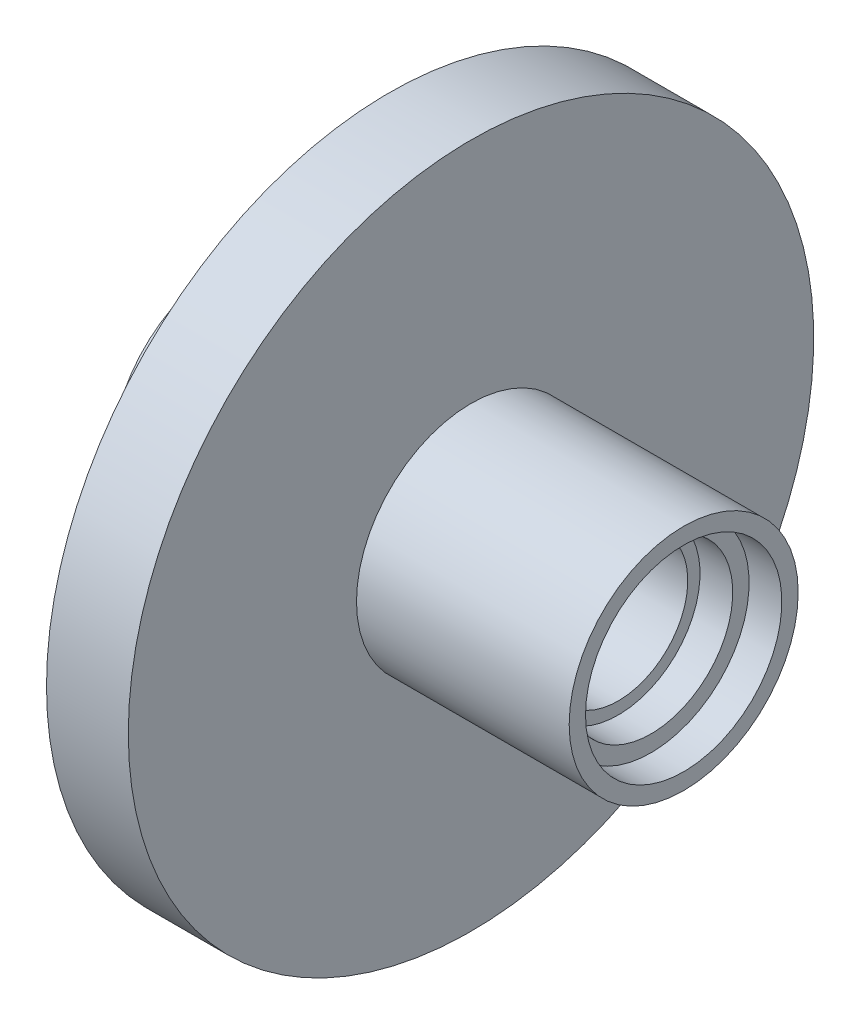
SolidWorks part; units mm, degrees
ref_plane "Front Plane" through (0, 0, 0) normal (0, 0, 1) x (1, 0, 0)
ref_plane "Top Plane" through (0, 0, 0) normal (0, 1, 0) x (1, 0, 0)
ref_plane "Right Plane" through (0, 0, 0) normal (1, 0, 0) x (0, 0, -1)
sketch "Sketch1" plane through (0, 0, 0) normal (0, 0, 1) x (1, 0, 0)
  line L0 (0, 0) -> (24.9448, 0) construction
  line L1 (-2.5, 20.95) -> (2.5, 20.95)
  line L2 (-2.5, 20.95) -> (-2.5, -20.95)
  line L3 (-2.5, -20.95) -> (2.5, -20.95)
  line L4 (2.5, 20.95) -> (2.5, -20.95)
  line L5 (-2.5, 20.95) -> (2.5, -20.95) construction
  line L6 (-2.5, -20.95) -> (2.5, 20.95) construction
  line L7 (-8.5, 0) -> (11.5, 0) construction
  line L8 (-5, 16.5) -> (-2.5, 16.5)
  line L9 (-5, 16.5) -> (-5, -16.5)
  line L10 (-5, -16.5) -> (-2.5, -16.5)
  line L11 (-2.5, 16.5) -> (-2.5, -16.5)
  line L12 (-5, 16.5) -> (-2.5, -16.5) construction
  line L13 (-5, -16.5) -> (-2.5, 16.5) construction
  line L14 (-12.5, 7) -> (-5, 7)
  line L15 (-12.5, 7) -> (-12.5, -7)
  line L16 (-12.5, -7) -> (-5, -7)
  line L17 (-5, 7) -> (-5, -7)
  line L18 (-12.5, 7) -> (-5, -7) construction
  line L19 (-12.5, -7) -> (-5, 7) construction
  line L20 (15.5, 7) -> (2.5, 7)
  line L21 (15.5, 7) -> (15.5, -7)
  line L22 (15.5, -7) -> (2.5, -7)
  line L23 (2.5, 7) -> (2.5, -7)
  line L24 (15.5, 7) -> (2.5, -7) construction
  line L25 (15.5, -7) -> (2.5, 7) construction
  line L26 (-8.5, 4.25) -> (11.5, 4.25)
  line L27 (-8.5, 4.25) -> (-8.5, -4.25)
  line L28 (-8.5, -4.25) -> (11.5, -4.25)
  line L29 (11.5, 4.25) -> (11.5, -4.25)
  line L32 (13.5, 5) -> (11.5, 5)
  line L33 (13.5, 5) -> (13.5, -5)
  line L34 (13.5, -5) -> (11.5, -5)
  line L35 (11.5, 5) -> (11.5, -5)
  line L36 (13.5, 5) -> (11.5, -5) construction
  line L37 (13.5, -5) -> (11.5, 5) construction
  line L38 (15.5, -6) -> (13.5, -6)
  line L39 (15.5, -6) -> (15.5, 6)
  line L40 (15.5, 6) -> (13.5, 6)
  line L41 (13.5, -6) -> (13.5, 6)
  line L42 (15.5, -6) -> (13.5, 6) construction
  line L43 (15.5, 6) -> (13.5, -6) construction
  line L44 (-10.5, 5) -> (-8.5, 5)
  line L45 (-10.5, 5) -> (-10.5, -5)
  line L46 (-10.5, -5) -> (-8.5, -5)
  line L47 (-8.5, 5) -> (-8.5, -5)
  line L48 (-10.5, 5) -> (-8.5, -5) construction
  line L49 (-10.5, -5) -> (-8.5, 5) construction
  line L50 (-12.5, 6) -> (-10.5, 6)
  line L51 (-12.5, 6) -> (-12.5, -6)
  line L52 (-12.5, -6) -> (-10.5, -6)
  line L53 (-10.5, 6) -> (-10.5, -6)
  line L54 (-12.5, 6) -> (-10.5, -6) construction
  line L55 (-12.5, -6) -> (-10.5, 6) construction
  point P0 (0, 0)
  point P6 (-3.75, 0)
  point P13 (-8.75, 0)
  point P18 (9, 0)
  point P23 (0, 0)
  point P28 (12.5, 0)
  point P33 (14.5, 0)
  point P38 (-9.5, 0)
  point P43 (-11.5, 0)
  dimension "D1" = 10
  dimension "D2" = 12
  dimension "D3" = 8.5
  dimension "D4" = 10
  dimension "D5" = 12
  dimension "D6" = 28
  dimension "D7" = 2
  dimension "D8" = 2
  dimension "D9" = 2
  dimension "D10" = 2
  dimension "D11" = 5
  dimension "D12" = 14
  dimension "D13" = 14
  dimension "D14" = 2.5
  dimension "D15" = 33
  dimension "D16" = 41.9
  dimension "D17" = 7.5
revolve "Revolve1" add sketch "Sketch1" angle 360 about L0
sketch "Sketch2" plane through (-5, 0, 0) normal (-1, 0, 0) x (0, 0, 1)
  line L0 (0, 0) -> (9.1924, 9.1924) construction
  line L1 (0, 0) -> (0, 6.5242) construction
  circle A0 centre (9.1924, 9.1924) radius 1.25
  dimension "D1" = 2.5
  dimension "D2" = 13
  dimension "D3" = 45
extrude "M2.5" cut sketch "Sketch2" against normal blind 5
pattern_circular "CirPattern1" count 4 over 360 about axis through (0, 0, 0) along (1, 0, 0) of "M2.5"
sketch "Sketch3" plane through (-12.5, 0, 0) normal (-1, 0, 0) x (0, 0, 1)
  line L0 (0, 0) -> (0, 3) construction
  line L1 (-1, 3) -> (1, 3)
  circle A0 centre (1, 3) radius 0.5
  circle A1 centre (-1, 3) radius 0.5
  point P6 (0, 3)
  dimension "D1" = 1
  dimension "D2" = 1
  dimension "D3" = 2
  dimension "D4" = 3
